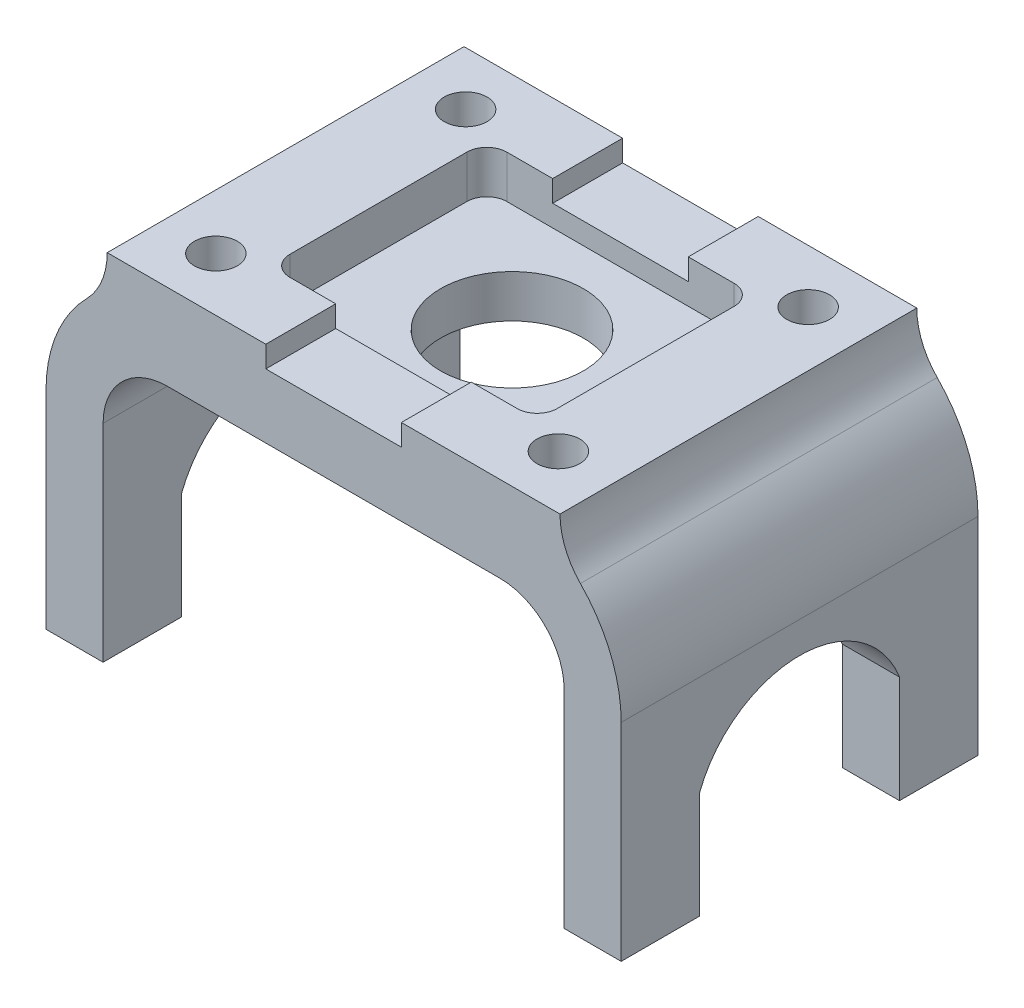
SolidWorks part; units mm, degrees
material "Plain Carbon Steel"
ref_plane "Front Plane" through (0, 0, 0) normal (0, 0, 1) x (1, 0, 0)
ref_plane "Top Plane" through (0, 0, 0) normal (0, 1, 0) x (1, 0, 0)
ref_plane "Right Plane" through (0, 0, 0) normal (1, 0, 0) x (0, 0, -1)
sketch "Sketch2" plane through (0, 0, 0) normal (0, 0, 1) x (1, 0, 0)
  line L0 (-29.591, 0) -> (29.591, 0)
  line L1 (41.021, -11.43) -> (41.021, -48.26)
  line L2 (41.021, -48.26) -> (51.181, -48.26)
  line L3 (51.181, -48.26) -> (51.181, -11.43)
  line L4 (40.2898, 15.24) -> (-40.2898, 15.24)
  line L5 (-51.181, -11.43) -> (-51.181, -48.26)
  line L6 (-51.181, -48.26) -> (-41.021, -48.26)
  line L7 (-41.021, -48.26) -> (-41.021, -11.43)
  line L8 (0, 0) -> (0, 94.6407) construction
  arc A0 (51.181, -11.43) -> (43.9202, 6.35) centre (25.781, -11.43) ccw
  arc A1 (43.9202, 6.35) -> (40.2898, 15.24) centre (52.9898, 15.24) cw
  arc A2 (-40.2898, 15.24) -> (-43.9202, 6.35) centre (-52.9898, 15.24) cw
  arc A3 (-43.9202, 6.35) -> (-51.181, -11.43) centre (-25.781, -11.43) ccw
  arc A4 (29.591, 0) -> (41.021, -11.43) centre (29.591, -11.43) cw
  arc A5 (-29.591, 0) -> (-41.021, -11.43) centre (-29.591, -11.43) ccw
  dimension "D1" = 36.83
  dimension "D4" = 12.7
  dimension "D5" = 25.4
  dimension "D2" = 10.16
  dimension "D3" = 15.24
  dimension "D6" = 82.042
  dimension "D7" = 63.5
extrude "Boss-Extrude1" add sketch "Sketch2" along normal mid plane 63.5
sketch "Sketch3" plane through (51.181, 0, 0) normal (1, 0, 0) x (0, 0, -1)
  line L0 (-17.78, -48.26) -> (17.78, -48.26)
  line L1 (-31.75, -48.26) -> (31.75, -48.26) construction
  line L2 (17.78, -48.26) -> (17.78, -29.21)
  line L3 (-17.78, -29.21) -> (-17.78, -48.26)
  arc A0 (17.78, -29.21) -> (-17.78, -29.21) centre (0, -36.0492) ccw
  dimension "D2" = 19.05
  dimension "D1" = 19.05
  dimension "D3" = 35.56
extrude "Cut-Extrude1" cut sketch "Sketch3" against normal through all
sketch "Sketch4" plane through (0, 15.24, 0) normal (0, 1, 0) x (1, 0, 0)
  line L0 (40.2898, 31.75) -> (-40.2898, 31.75) construction
  line L1 (-20.2238, 19.304) -> (20.2238, 19.304)
  line L2 (-23.7798, 15.748) -> (-23.7798, -15.748)
  line L3 (-20.2238, -19.304) -> (20.2238, -19.304)
  line L4 (23.7798, 15.748) -> (23.7798, -15.748)
  line L5 (-23.7798, -19.304) -> (23.7798, 19.304) construction
  line L6 (-40.2898, -31.75) -> (-40.2898, 31.75) construction
  arc A0 (-23.7798, -15.748) -> (-20.2238, -19.304) centre (-20.2238, -15.748) ccw
  arc A1 (20.2238, -19.304) -> (23.7798, -15.748) centre (20.2238, -15.748) ccw
  arc A2 (20.2238, 19.304) -> (23.7798, 15.748) centre (20.2238, 15.748) cw
  arc A3 (-20.2238, 19.304) -> (-23.7798, 15.748) centre (-20.2238, 15.748) ccw
  dimension "D3" = 3.556
  dimension "D1" = 12.446
  dimension "D2" = 16.51
extrude "Cut-Extrude2" cut sketch "Sketch4" against normal blind 7.62
sketch "Sketch5" plane through (0, 0, 31.75) normal (0, 0, 1) x (1, 0, 0)
  line L0 (0, 0) -> (0, 29.0489) construction
  line L1 (-29.591, 0) -> (29.591, 0) construction
  line L2 (40.2898, 15.24) -> (-40.2898, 15.24) construction
  line L3 (12.065, 15.24) -> (-12.065, 15.24)
  line L4 (12.065, 15.24) -> (12.065, 11.43)
  line L5 (12.065, 11.43) -> (-12.065, 11.43)
  line L6 (-12.065, 15.24) -> (-12.065, 11.43)
  dimension "D1" = 24.13
  dimension "D2" = 3.81
extrude "Cut-Extrude3" cut sketch "Sketch5" against normal through all
sketch "Sketch6" plane through (0, 7.62, 0) normal (0, 1, 0) x (1, 0, 0)
  circle A0 centre (0, 0) radius 12.7
  dimension "D1" = 25.4
extrude "Cut-Extrude4" cut sketch "Sketch6" against normal up to next
sketch "Sketch7" plane through (0, 15.24, 0) normal (0, 1, 0) x (1, 0, 0)
  line L0 (-57.8306, 0) -> (65.0092, 0) construction
  line L1 (0, -38.3252) -> (0, 42.5913) construction
  circle A0 centre (-30.48, 22.225) radius 3.81
  circle A1 centre (30.48, 22.225) radius 3.81
  circle A2 centre (30.48, -22.225) radius 3.81
  circle A3 centre (-30.48, -22.225) radius 3.81
  dimension "D1" = 7.62
  dimension "D2" = 60.96
  dimension "D3" = 44.45
extrude "Cut-Extrude5" cut sketch "Sketch7" against normal up to next
